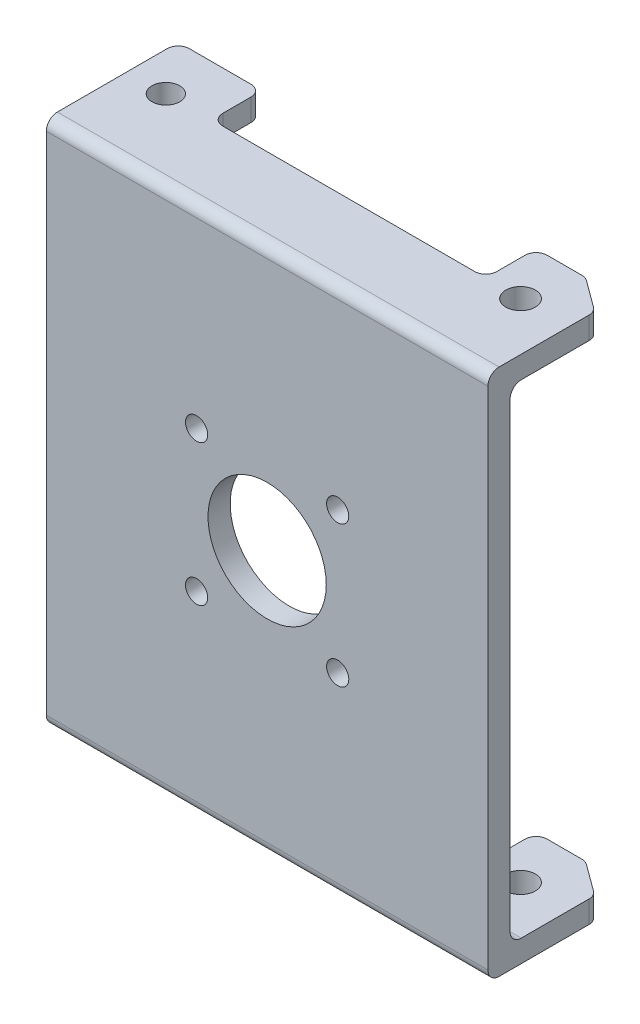
SolidWorks part; units mm, degrees
ref_plane "Front Plane" through (0, 0, 0) normal (0, 0, 1) x (1, 0, 0)
ref_plane "Top Plane" through (0, 0, 0) normal (0, 1, 0) x (1, 0, 0)
ref_plane "Right Plane" through (0, 0, 0) normal (1, 0, 0) x (0, 0, -1)
sketch "Sketch1" plane through (0, 0, 0) normal (0, 0, 1) x (1, 0, 0)
  line L1 (-14.94, -17.855) -> (14.94, -17.855)
  line L2 (-14.94, -17.855) -> (-14.94, 17.855)
  line L3 (-14.94, 17.855) -> (14.94, 17.855)
  line L4 (14.94, -17.855) -> (14.94, 17.855)
  line L5 (-14.94, -17.855) -> (14.94, 17.855) construction
  line L6 (-14.94, 17.855) -> (14.94, -17.855) construction
  circle A0 centre (0, 0) radius 4
  circle A1 centre (4.773, 4.773) radius 0.75
  circle A2 centre (4.773, -4.773) radius 0.75
  circle A3 centre (-4.773, -4.773) radius 0.75
  circle A4 centre (-4.773, 4.773) radius 0.75
  point P0 (0, 0)
extrude "Boss-Extrude1" add sketch "Sketch1" along normal blind 1.5
sketch "Sketch2" plane through (0, 17.855, 0) normal (0, 1, 0) x (1, 0, 0)
  line L1 (-14.94, 7.426) -> (-9.27, 7.426)
  line L2 (-9.27, 7.426) -> (-9.27, 4.0193)
  line L3 (-9.27, 4.0193) -> (9.27, 4.0193)
  line L4 (9.27, 7.426) -> (9.27, 4.0193)
  line L5 (9.27, 7.426) -> (12.62, 7.426)
  line L6 (14.94, -1.5) -> (14.94, 5.7227)
  line L8 (-14.94, -1.5) -> (14.94, -1.5)
  line L9 (-14.94, -1.5) -> (-14.94, 7.426)
  line L10 (12.62, 7.426) -> (14.94, 5.7227)
  circle A3 centre (-12.34, 3.986) radius 0.94
  arc A7 (12.66, 3.986) -> (10.66, 3.986) centre (11.66, 3.986) ccw
  arc A8 (10.66, 3.986) -> (12.66, 3.986) centre (11.66, 3.986) ccw
  arc A9 (12.66, 3.986) -> (10.66, 3.986) centre (11.66, 3.986) ccw
  arc A10 (10.66, 3.986) -> (12.66, 3.986) centre (11.66, 3.986) ccw
  dimension "D1" = 0
extrude "Boss-Extrude2" add sketch "Sketch2" against normal blind 1.5
sketch "Sketch3" plane through (0, -17.855, 0) normal (0, -1, 0) x (1, 0, 0)
  line L1 (-14.94, 1.5) -> (14.94, 1.5) construction
  line L3 (9.27, -7.426) -> (9.27, -4.0193) construction
  line L4 (12.62, -7.426) -> (9.27, -7.426) construction
  line L5 (14.94, -5.7227) -> (12.62, -7.426) construction
  line L9 (-9.27, -4.0193) -> (-9.27, -7.426) construction
  line L10 (9.27, -4.0193) -> (-9.27, -4.0193) construction
  line L12 (-14.94, 1.5) -> (14.94, 1.5)
  line L14 (9.27, -7.426) -> (9.27, -4.0193)
  line L15 (12.62, -7.426) -> (9.27, -7.426)
  line L16 (14.94, -5.7227) -> (12.62, -7.426)
  line L21 (9.27, -4.0193) -> (-5.44, -4.0193)
  line L22 (-14.94, -7.426) -> (-5.44, -7.426)
  line L23 (-5.44, -7.426) -> (-5.44, -4.0193)
  line L24 (-14.94, 1.5) -> (-14.94, -7.426)
  line L25 (14.94, 1.5) -> (14.94, -5.7227)
  circle A3 centre (11.66, -3.986) radius 1 construction
  circle A5 centre (11.66, -3.986) radius 1
  circle A7 centre (-8.34, -3.986) radius 1
extrude "Boss-Extrude3" add sketch "Sketch3" against normal blind 1.5
fillet "Fillet1" radius 0.75 18 edges at (0, 16.355, 0) (0, -16.355, 0) (14.94, -17.105, -5.7227) (12.62, -17.105, -7.426) (9.27, -17.105, -7.426) (9.27, -17.105, -4.0193) (-5.44, -17.105, -4.0193) (-5.44, -17.105, -7.426) (-14.94, -17.105, -7.426) (-14.94, 17.105, -7.426) (14.94, 17.105, -5.7227) (12.62, 17.105, -7.426) (-9.27, 17.105, -4.0193) (9.27, 17.105, -4.0193) (9.27, 17.105, -7.426) (-9.27, 17.105, -7.426) (0, -17.855, 1.5) (0, 17.855, 1.5)
